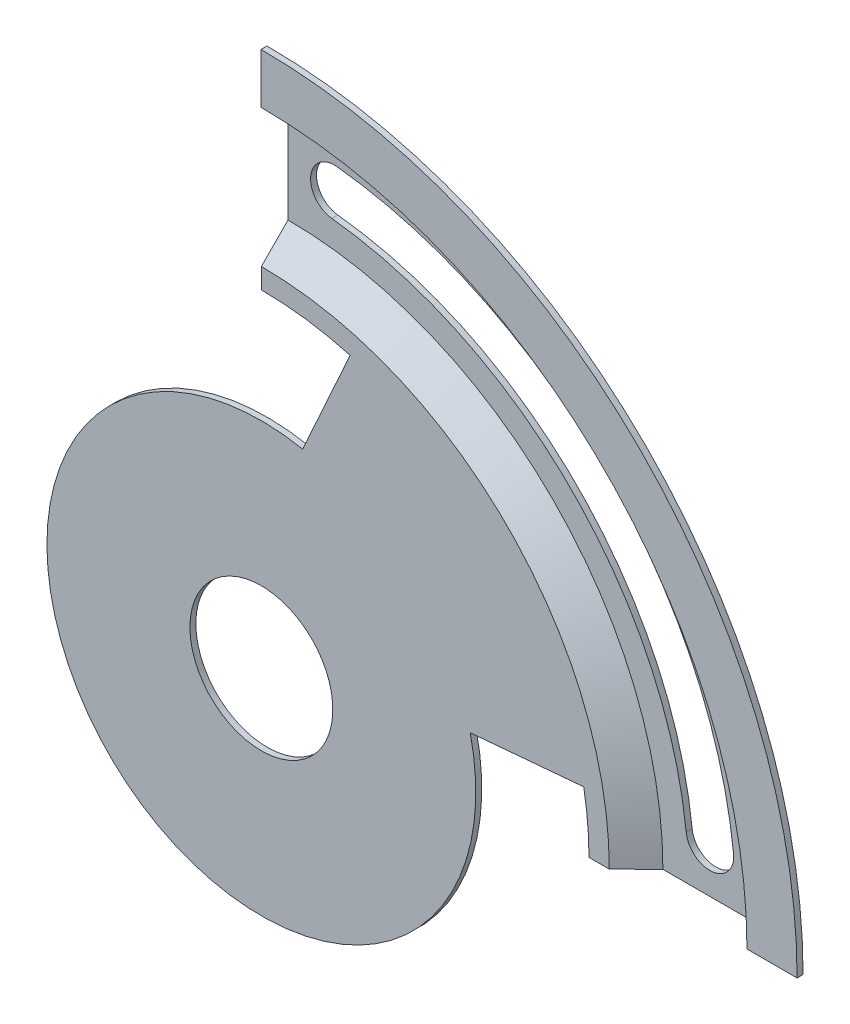
SolidWorks part; units mm, degrees
material "1023 Carbon Steel Sheet (SS)"
ref_plane "Front Plane" through (0, 0, 0) normal (0, 0, 1) x (1, 0, 0)
ref_plane "Top Plane" through (0, 0, 0) normal (0, 1, 0) x (1, 0, 0)
ref_plane "Right Plane" through (0, 0, 0) normal (1, 0, 0) x (0, 0, -1)
sketch "Sketch1" plane through (0, 0, 0) normal (0, 1, 0) x (1, 0, 0)
  line L0 (15.7283, -17.7674) -> (7.7283, -17.7674)
  line L1 (7.7283, -17.7674) -> (3.2585, -13.2372)
  line L2 (3.2585, -13.2372) -> (-11.7415, -13.2372)
  line L3 (-11.7415, -13.2372) -> (-16.2716, -17.707)
  line L4 (-16.2716, -17.707) -> (-19.2716, -17.707)
  line L5 (-74.2717, -17.707) -> (-74.2717, -49.8443)
  line L6 (15.7283, -18.7674) -> (7.3102, -18.7674)
  line L7 (7.3102, -18.7674) -> (2.8404, -14.2372)
  line L8 (2.8404, -14.2372) -> (-11.3312, -14.2372)
  line L9 (-11.3312, -14.2372) -> (-15.8613, -18.707)
  line L10 (-15.8613, -18.707) -> (-19.2716, -18.707)
  line L11 (15.7283, -17.7674) -> (15.7283, -18.7674)
  line L12 (-19.2716, -17.707) -> (-19.2716, -18.707)
  dimension "D1" = 35
  dimension "D2" = 15
  dimension "D3" = 3
  dimension "D4" = 8
  dimension "D5" = 90
  dimension "D6" = 1
revolve "Revolve1" add sketch "Sketch1" angle 90 about L5
sketch "Sketch2" plane through (0, 0, 17.707) normal (0, 0, -1) x (-1, 0, 0)
  line L0 (67.343, 35.3269) -> (59.3717, 52.9433)
  line L2 (39.2081, 8.1576) -> (20.156, 9.8231)
  circle A0 centre (74.2717, 0) radius 12
  arc A1 (39.2081, 8.1576) -> (67.343, 35.3269) centre (74.2717, 0) ccw
  arc A2 (74.2717, 55.0001) -> (19.2716, 0) centre (74.2717, 0) ccw construction
  arc A3 (59.3717, 52.9433) -> (20.156, 9.8231) centre (74.2717, 0) ccw
  dimension "D1" = 24
  dimension "D2" = 72
extrude "Boss-Extrude1" add sketch "Sketch2" against normal blind 1
sketch "Sketch3" plane through (0, 0, 13.2372) normal (0, 0, -1) x (-1, 0, 0)
  line L1 (74.2717, 0) -> (33.2594, 41.0122)
  arc A0 (66.2155, 74.8209) -> (-0.5492, 8.0562) centre (74.2717, 0) ccw
  arc A1 (66.9213, 66.8505) -> (7.4212, 7.3503) centre (74.2717, 0) ccw
  arc A2 (66.9213, 66.8505) -> (66.2155, 74.8209) centre (66.4839, 70.8282) ccw
  arc A3 (74.2717, 58.0001) -> (16.2716, 0) centre (74.2717, 0) ccw construction
  arc A4 (7.4212, 7.3503) -> (-0.5492, 8.0562) centre (3.4435, 7.7877) cw
  circle A5 centre (74.2717, 0) radius 67.2534 construction
  circle A6 centre (74.2717, 0) radius 75.2534 construction
  dimension "D1" = 8
extrude "Cut-Extrude1" cut sketch "Sketch3" against normal through all both and the other way through all contours A4 A1 A2 A0
